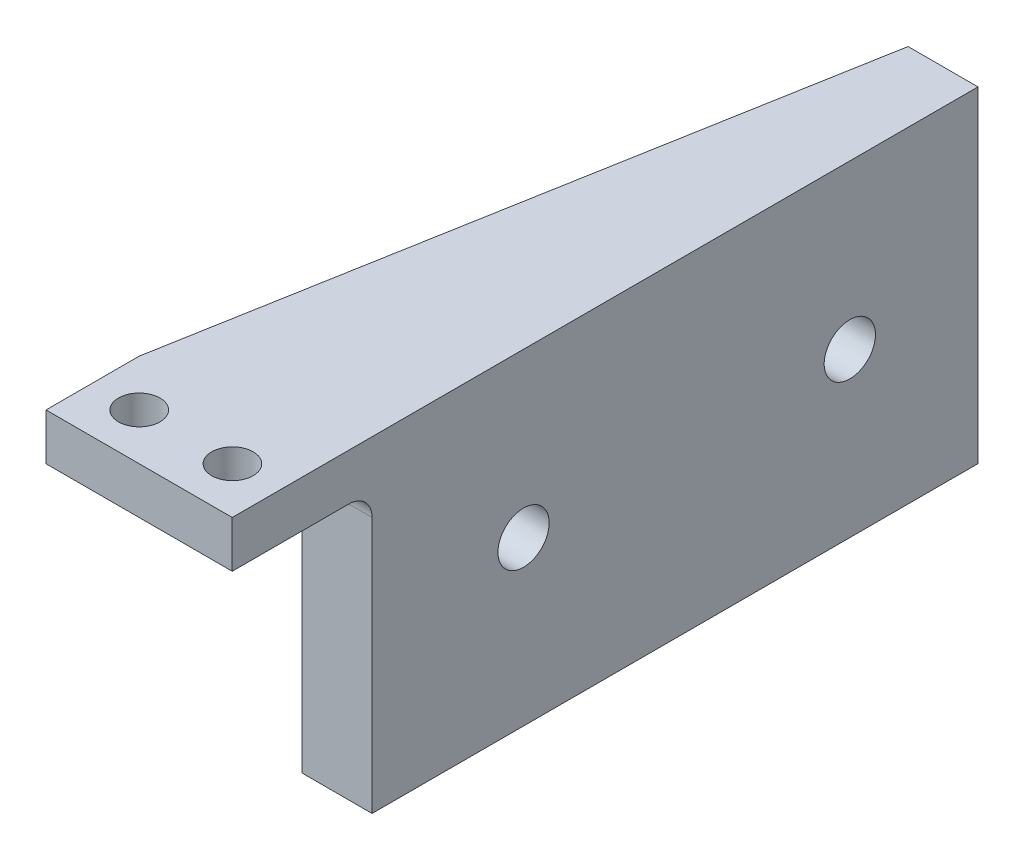
SolidWorks part; units mm, degrees
ref_plane "Front Plane" through (0, 0, 0) normal (0, 0, 1) x (1, 0, 0)
ref_plane "Top Plane" through (0, 0, 0) normal (0, 1, 0) x (1, 0, 0)
ref_plane "Right Plane" through (0, 0, 0) normal (1, 0, 0) x (0, 0, -1)
sketch "Sketch1" plane through (0, 0, 0) normal (0, 1, 0) x (1, 0, 0)
  line L0 (-2.54, 2.54) -> (3.7986, 38.1)
  line L1 (-2.54, -2.54) -> (7.6086, -2.54)
  line L2 (-2.54, -2.54) -> (-2.54, 2.54)
  line L3 (-2.54, 2.54) -> (7.6086, 2.54) construction
  line L4 (7.6086, -2.54) -> (7.6086, 2.54)
  line L5 (3.7986, 38.1) -> (7.6086, 38.1)
  line L6 (7.6086, 38.1) -> (7.6086, 2.54)
  circle A0 centre (0, 0) radius 1.1303
  circle A1 centre (5.08, 0) radius 1.1303
  dimension "D2" = 2.2606
  dimension "D1" = 5.08
  dimension "D3" = 2.54
  dimension "D4" = 2.5286
  dimension "D5" = 2.54
  dimension "D6" = 2.54
  dimension "D7" = 40.64
  dimension "D8" = 3.81
extrude "Boss-Extrude1" add sketch "Sketch1" along normal blind 2.54
sketch "Sketch2" plane through (0, 0, 0) normal (0, -1, 0) x (1, 0, 0)
  line L1 (7.6086, -38.1) -> (3.7986, -38.1)
  line L2 (7.6086, -38.1) -> (7.6086, -5.08)
  line L3 (7.6086, -5.08) -> (3.7986, -5.08)
  line L4 (3.7986, -38.1) -> (3.7986, -5.08)
  line L5 (-2.54, 2.54) -> (7.6086, 2.54) construction
  dimension "D1" = 7.62
extrude "Boss-Extrude2" add sketch "Sketch2" along normal blind 15.24
fillet "Fillet1" radius 1.27 2 edges at (5.7036, 0, -5.08) (3.7986, 0, -21.59)
ref_plane "Plane1" through (0, 0, -34.9253) normal (0, 0, -1) x (-1, 0, 0)
ref_plane "Plane2" through (0, 0, -9.5253) normal (0, 0, -1) x (-1, 0, 0)
sketch "Sketch3" plane through (7.6086, 0, 0) normal (1, 0, 0) x (0, 0, -1)
  line L0 (38.1, 2.54) -> (38.1, -15.24) construction
  line L1 (9.5253, -2.0955) -> (9.5253, 2.0955) construction
  line L2 (34.9253, -2.0955) -> (34.9253, 2.0955) construction
  circle A0 centre (13.3353, -6.35) radius 1.397
  circle A1 centre (31.1153, -6.35) radius 1.397
  point P7 (38.1, -6.35)
  dimension "D1" = 2.794
  dimension "D2" = 3.81
  dimension "D3" = 3.81
extrude "Cut-Extrude1" cut sketch "Sketch3" against normal blind 12.7
